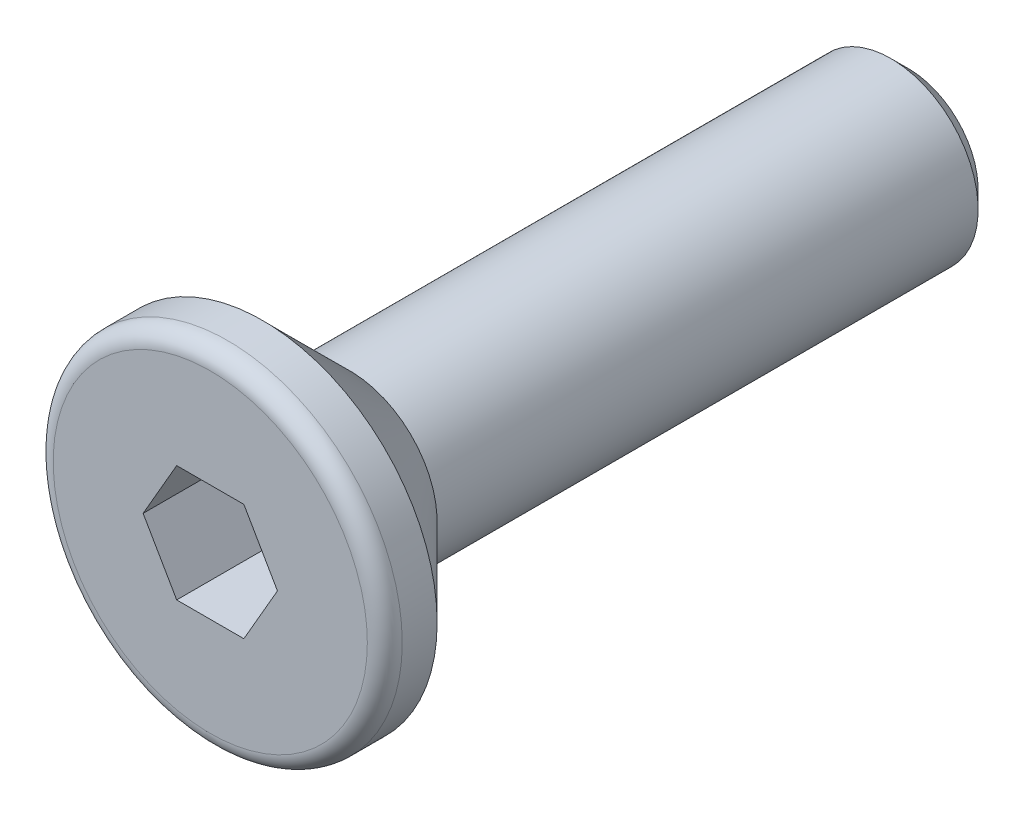
SolidWorks part; units mm, degrees
ref_plane "前视基准面" through (0, 0, 0) normal (0, 0, 1) x (1, 0, 0)
ref_plane "上视基准面" through (0, 0, 0) normal (0, 1, 0) x (1, 0, 0)
ref_plane "右视基准面" through (0, 0, 0) normal (1, 0, 0) x (0, 0, -1)
sketch "草图1" plane through (0, 0, 0) normal (1, 0, 0) x (0, 0, -1)
  line L0 (-6, 0) -> (-6, 3)
  line L1 (-6, 3) -> (-5.1, 3)
  line L2 (-5.1, 3) -> (-3.6, 1.5)
  line L3 (-3.6, 1.5) -> (5.7, 1.5)
  line L4 (5.7, 1.5) -> (6, 1.2)
  line L5 (6, 1.2) -> (6, 0)
  line L6 (6, 0) -> (-6, 0)
  dimension "D1" = 12
  dimension "D2" = 3
  dimension "D3" = 45
  dimension "D4" = 0.3
  dimension "D5" = 2.4
  dimension "D6" = 1.5
revolve "旋转1" add sketch "草图1" angle 360 about L6
sketch "草图2" plane through (0, 0, 6) normal (0, 0, 1) x (1, 0, 0)
  line L1 (1.1547, 0) -> (0.5774, 1)
  line L2 (0.5774, 1) -> (-0.5774, 1)
  line L3 (-0.5774, 1) -> (-1.1547, 0)
  line L4 (-1.1547, 0) -> (-0.5774, -1)
  line L5 (-0.5774, -1) -> (0.5774, -1)
  line L6 (0.5774, -1) -> (1.1547, 0)
  circle A0 centre (0, 0) radius 1 construction
  dimension "D1" = 2
extrude "切除-拉伸1" cut sketch "草图2" against normal blind 1.5
fillet "圆角1" radius 0.3 1 edges at (-3, 0, 6)
